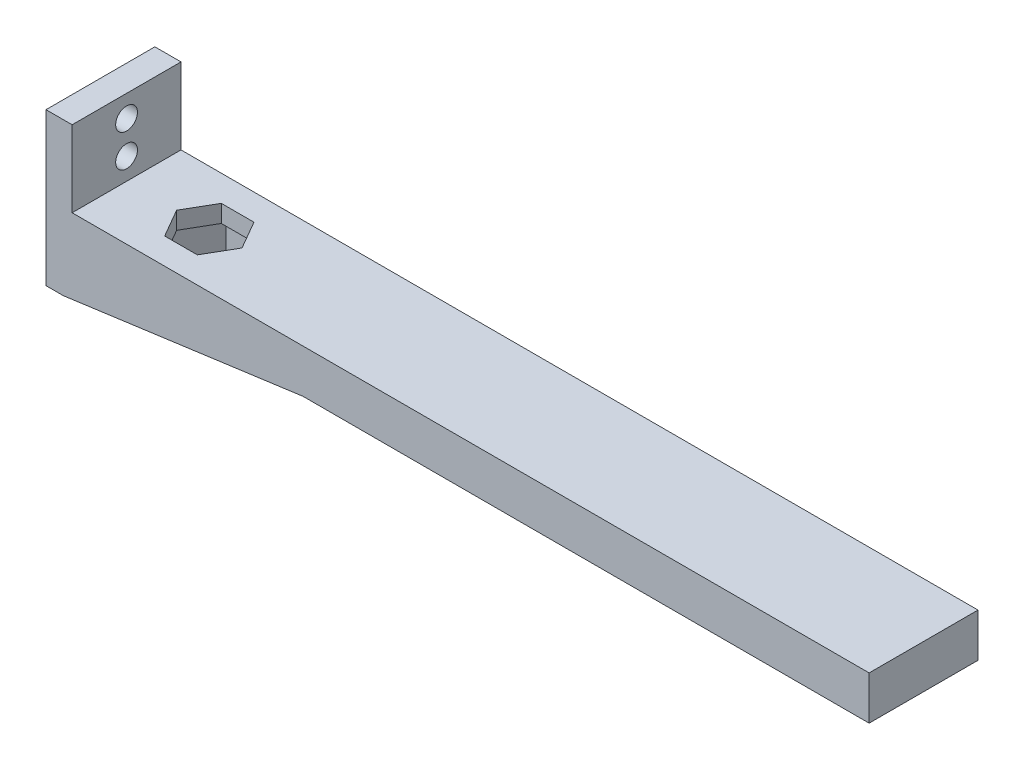
SolidWorks part; units mm, degrees
ref_plane "Alzado" through (0, 0, 0) normal (0, 0, 1) x (1, 0, 0)
ref_plane "Planta" through (0, 0, 0) normal (0, 1, 0) x (1, 0, 0)
ref_plane "Vista lateral" through (0, 0, 0) normal (1, 0, 0) x (0, 0, -1)
sketch "Croquis3" plane through (0, 0, 0) normal (1, 0, 0) x (0, 0, -1)
  line L1 (-8.1731, 20.3125) -> (16.8269, 20.3125)
  line L2 (-8.1731, 20.3125) -> (-8.1731, -14.6875)
  line L3 (-8.1731, -14.6875) -> (16.8269, -14.6875)
  line L4 (16.8269, 20.3125) -> (16.8269, -14.6875)
  dimension "D1" = 25
  dimension "D2" = 35
extrude "Saliente-Extruir2" add sketch "Croquis3" along normal blind 4
sketch "Croquis5" plane through (4, 0, 0) normal (1, 0, 0) x (0, 0, -1)
  line L0 (16.8269, -14.6875) -> (16.8269, 20.3125) construction
  line L1 (-8.1731, 20.3125) -> (16.8269, 20.3125)
  line L2 (-8.1731, 20.3125) -> (-8.1731, 2.8125)
  line L3 (-8.1731, 2.8125) -> (16.8269, 2.8125)
  line L4 (16.8269, 20.3125) -> (16.8269, 2.8125)
extrude "Saliente-Extruir3" add sketch "Croquis5" along normal blind 2
sketch "Croquis7" plane through (4, 0, 0) normal (1, 0, 0) x (0, 0, -1)
  line L0 (16.8269, -14.6875) -> (16.8269, 2.8125) construction
  line L1 (-8.1731, 2.8125) -> (16.8269, 2.8125)
  line L2 (-8.1731, 2.8125) -> (-8.1731, -7.1875)
  line L3 (-8.1731, -7.1875) -> (16.8269, -7.1875)
  line L4 (16.8269, 2.8125) -> (16.8269, -7.1875)
  dimension "D1" = 10
extrude "Saliente-Extruir5" add sketch "Croquis7" along normal blind 55
sketch "Croquis8" plane through (6, 0, 0) normal (1, 0, 0) x (0, 0, -1)
  line L0 (16.8269, 20.3125) -> (-8.1731, 20.3125) construction
  circle A0 centre (4.3269, 15.3125) radius 2.5
  circle A1 centre (4.3269, 7.8125) radius 2.5
  dimension "D1" = 5
  dimension "D2" = 5
  dimension "D3" = 7.5
  dimension "D4" = 5
extrude "Cortar-Extruir1" cut sketch "Croquis8" against normal blind 55
sketch "Croquis9" plane through (0, 2.8125, 0) normal (0, 1, 0) x (1, 0, 0)
  line L0 (59, 16.8269) -> (6, 16.8269) construction
  line L1 (32.5056, 4.3269) -> (28.7528, 10.8269)
  line L2 (28.7528, 10.8269) -> (21.2472, 10.8269)
  line L3 (21.2472, 10.8269) -> (17.4944, 4.3269)
  line L4 (17.4944, 4.3269) -> (21.2472, -2.1731)
  line L5 (21.2472, -2.1731) -> (28.7528, -2.1731)
  line L6 (28.7528, -2.1731) -> (32.5056, 4.3269)
  line L9 (0, 16.8269) -> (0, -8.1731) construction
  circle A0 centre (25, 4.3269) radius 6.5 construction
  dimension "D1" = 13
  dimension "D2" = 25
sketch "Croquis10" plane through (0, 0, 8.1731) normal (0, 0, 1) x (1, 0, 0)
  line L0 (4, -14.6875) -> (59, -7.1875)
  line L1 (59, -7.1875) -> (4, -7.1875)
  line L2 (4, -7.1875) -> (4, -14.6875)
extrude "Saliente-Extruir6" add sketch "Croquis10" against normal through all
extrude "Cortar-Extruir3" cut sketch "Croquis9" against normal blind 4
sketch "Croquis11" plane through (59, 0, 0) normal (1, 0, 0) x (0, 0, -1)
  line L2 (16.8269, -7.1875) -> (16.8269, 2.8125) construction
  line L6 (-8.1731, 2.8125) -> (16.8269, 2.8125) construction
  circle A0 centre (-1.9231, -2.1875) radius 2
  circle A1 centre (10.5769, -2.1875) radius 2
  dimension "D1" = 4
  dimension "D2" = 4
  dimension "D3" = 12.5
  dimension "D4" = 6.25
  dimension "D5" = 5
extrude "Cortar-Extruir4" cut sketch "Croquis11" against normal blind 20
sketch "Croquis12" plane through (0, -1.1875, 0) normal (0, 1, 0) x (1, 0, 0)
  line L0 (28.7528, 10.8269) -> (21.2472, 10.8269) construction
  line L1 (30.2539, 13.4269) -> (19.7461, 13.4269)
  line L2 (19.7461, 13.4269) -> (14.4922, 4.3269)
  line L3 (14.4922, 4.3269) -> (19.7461, -4.7731)
  line L4 (19.7461, -4.7731) -> (30.2539, -4.7731)
  line L5 (30.2539, -4.7731) -> (35.5078, 4.3269)
  line L6 (35.5078, 4.3269) -> (30.2539, 13.4269)
  line L7 (0, 16.8269) -> (0, -8.1731) construction
  circle A0 centre (25, 4.3269) radius 9.1 construction
  dimension "D1" = 18.2
  dimension "D2" = 25
extrude "Cortar-Extruir5" cut sketch "Croquis12" against normal blind 45
sketch "Croquis13" plane through (59, 0, 0) normal (1, 0, 0) x (0, 0, -1)
  line L1 (-8.1731, -7.1875) -> (16.8269, -7.1875)
  line L2 (-8.1731, -7.1875) -> (-8.1731, 2.8125)
  line L3 (-8.1731, 2.8125) -> (16.8269, 2.8125)
  line L4 (16.8269, -7.1875) -> (16.8269, 2.8125)
extrude "Saliente-Extruir7" add sketch "Croquis13" along normal blind 130
